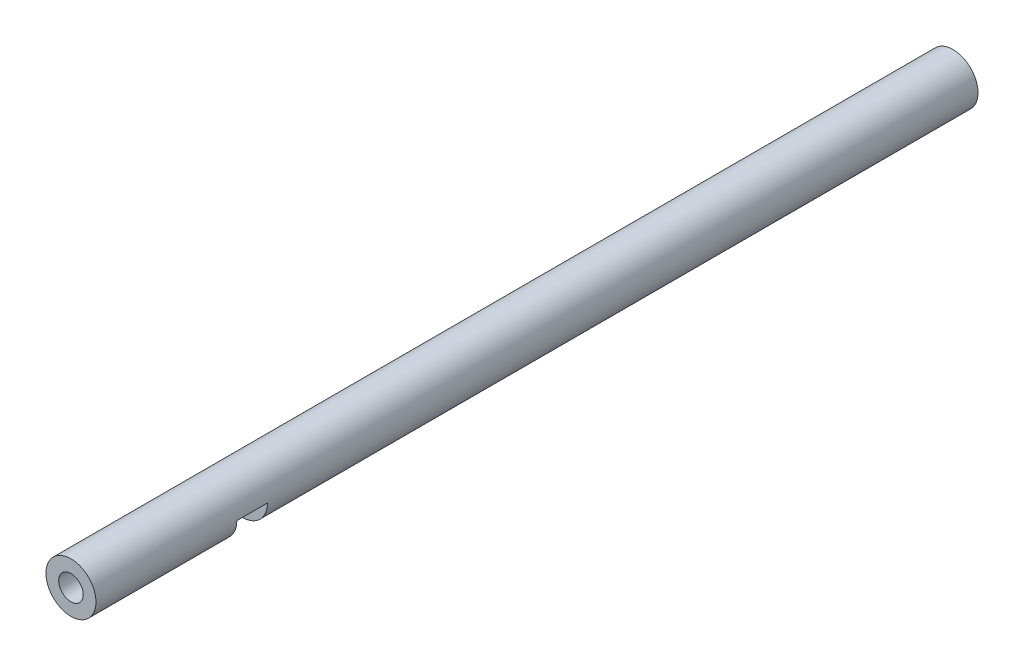
SolidWorks part; units mm, degrees
ref_plane "Front Plane" through (0, 0, 0) normal (0, 0, 1) x (1, 0, 0)
ref_plane "Top Plane" through (0, 0, 0) normal (0, 1, 0) x (1, 0, 0)
ref_plane "Right Plane" through (0, 0, 0) normal (1, 0, 0) x (0, 0, -1)
sketch "Sketch1" plane through (0, 0, 0) normal (0, 0, 1) x (1, 0, 0)
  circle A0 centre (0, 0) radius 6.477
  circle A1 centre (0, 0) radius 3.175
  dimension "D1" = 12.954
  dimension "D2" = 6.35
extrude "Boss-Extrude1" add sketch "Sketch1" along normal blind 228.6
sketch "Sketch2" plane through (0, 0, 0) normal (0, 1, 0) x (1, 0, 0)
  line L1 (-6.477, -192.0875) -> (6.477, -192.0875)
  line L2 (-6.477, -192.0875) -> (-6.477, -184.15)
  line L3 (-6.477, -184.15) -> (6.477, -184.15)
  line L4 (6.477, -192.0875) -> (6.477, -184.15)
  line L5 (-6.477, 0) -> (-6.477, -228.6) construction
  dimension "D1" = 184.15
  dimension "D2" = 12.954
  dimension "D3" = 7.9375
  dimension "D4" = 0
extrude "Cut-Extrude1" cut sketch "Sketch2" against normal through all
